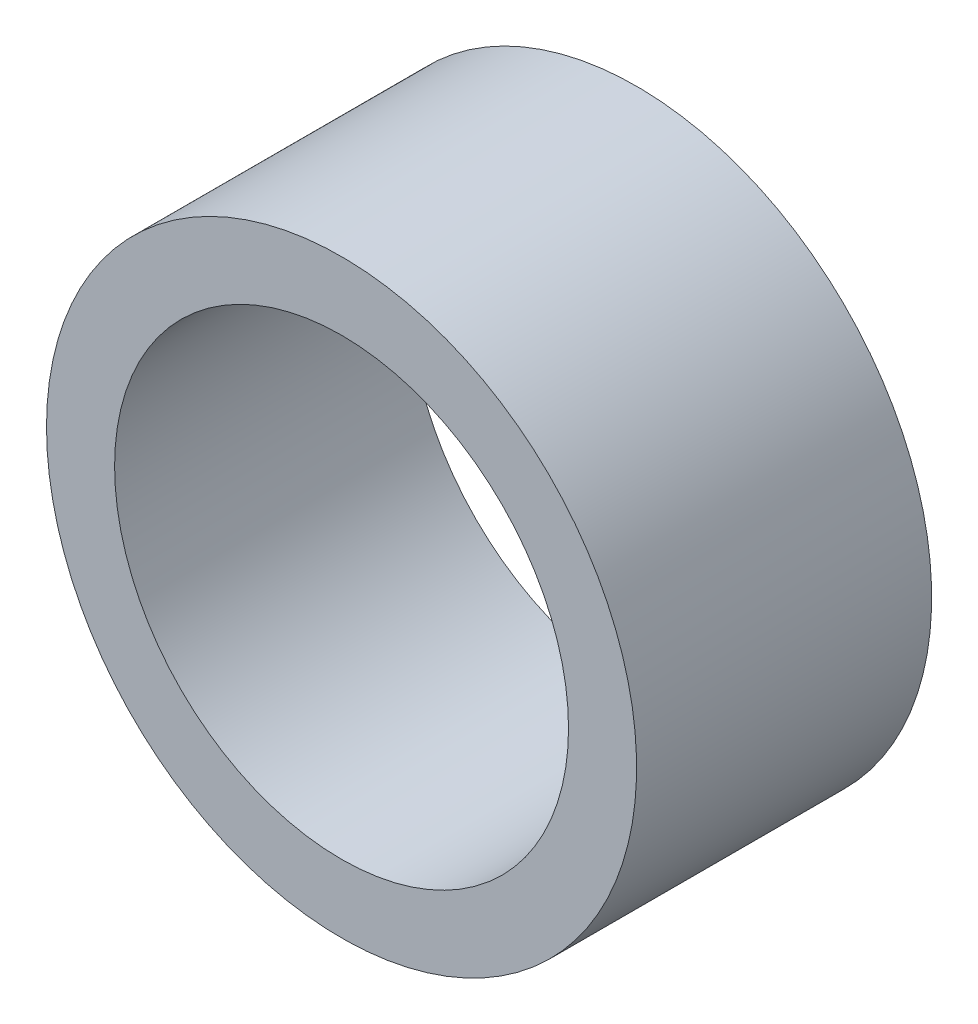
SolidWorks part; units mm, degrees
material "Caucho de silicio"
ref_plane "Alzado" through (0, 0, 0) normal (0, 0, 1) x (1, 0, 0)
ref_plane "Planta" through (0, 0, 0) normal (0, 1, 0) x (1, 0, 0)
ref_plane "Vista lateral" through (0, 0, 0) normal (1, 0, 0) x (0, 0, -1)
sketch "Croquis1" plane through (0, 0, 0) normal (0, 0, 1) x (1, 0, 0)
  circle A0 centre (0, 0) radius 20
  circle A1 centre (0, 0) radius 26
  dimension "D1" = 52
  dimension "D2" = 40
extrude "Saliente-Extruir1" add sketch "Croquis1" along normal blind 26
